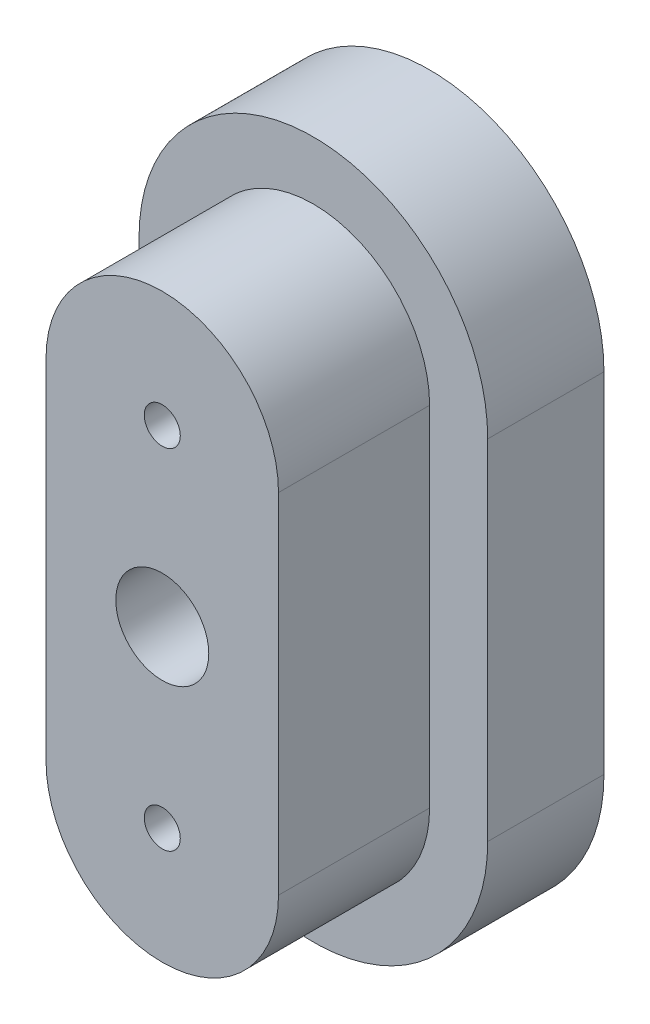
SolidWorks part; units mm, degrees
ref_plane "Front Plane" through (0, 0, 0) normal (0, 0, 1) x (1, 0, 0)
ref_plane "Top Plane" through (0, 0, 0) normal (0, 1, 0) x (1, 0, 0)
ref_plane "Right Plane" through (0, 0, 0) normal (1, 0, 0) x (0, 0, -1)
sketch "Sketch1" plane through (0, 0, 0) normal (0, 0, 1) x (1, 0, 0)
  line L0 (0, -4.7863) -> (0, 25.2137) construction
  line L1 (-10, -4.7863) -> (-10, 25.2137)
  line L2 (10, -4.7863) -> (10, 25.2137)
  arc A0 (-10, -4.7863) -> (10, -4.7863) centre (0, -4.7863) ccw
  arc A1 (10, 25.2137) -> (-10, 25.2137) centre (0, 25.2137) ccw
  point P2 (0, 10.2137)
  dimension "D1" = 0
  dimension "D2" = 30
  dimension "D3" = 10
extrude "Boss-Extrude1" add sketch "Sketch1" along normal blind 23
sketch "Sketch2" plane through (0, 0, 23) normal (0, 0, 1) x (1, 0, 0)
  line L0 (-10, 10.2137) -> (10, 10.2137) construction
  line L1 (-10, 25.2137) -> (-10, -4.7863) construction
  line L2 (10, -4.7863) -> (10, 25.2137) construction
  line L3 (0, 10.2137) -> (0, 25.2137) construction
  line L4 (0, 10.2137) -> (0, -4.7863) construction
  circle A0 centre (0, 25.2137) radius 1.55
  circle A1 centre (0, -4.7863) radius 1.55
  dimension "D1" = 3.1
  dimension "D2" = 3.1
  dimension "D4" = 15
  dimension "D5" = 15
extrude "Cut-Extrude1" cut sketch "Sketch2" against normal blind 30
sketch "Sketch3" plane through (0, 0, 0) normal (0, 0, -1) x (-1, 0, 0)
  line L0 (-10, 25.2137) -> (-10, -4.7863)
  line L1 (-10, 10.2137) -> (-15, 10.2137) construction
  line L2 (-15, 25.2137) -> (-15, -4.7863)
  line L3 (0, 35.2137) -> (0, -14.7863) construction
  line L4 (10, 25.2137) -> (10, -4.7863)
  line L5 (15, 25.2137) -> (15, -4.7863)
  arc A0 (10, 25.2137) -> (-10, 25.2137) centre (0, 25.2137) ccw construction
  arc A1 (-10, -4.7863) -> (10, -4.7863) centre (0, -4.7863) ccw construction
  arc A2 (-10, 25.2137) -> (10, 25.2137) centre (0, 25.2137) cw
  arc A3 (10, -4.7863) -> (-10, -4.7863) centre (0, -4.7863) cw
  arc A4 (-15, -4.7863) -> (15, -4.7863) centre (0, -4.7863) ccw
  arc A5 (15, 25.2137) -> (-15, 25.2137) centre (0, 25.2137) ccw
extrude "Boss-Extrude2" add sketch "Sketch3" against normal blind 10
sketch "Sketch5" plane through (0, 0, 23) normal (0, 0, 1) x (1, 0, 0)
  line L0 (10, -4.7863) -> (10, 25.2137) construction
  circle A0 centre (0, 10.2137) radius 4
  circle A2 centre (0, 25.2137) radius 1.55 construction
  dimension "D1" = 15
  dimension "D2" = 10
  dimension "D3" = 8
extrude "Cut-Extrude3" cut sketch "Sketch5" against normal blind 70
sketch "Esquisse1" plane through (0, 0, 0) normal (0, 0, -1) x (-1, 0, 0)
  circle A0 centre (0, 25.2137) radius 4.15
  circle A1 centre (0, -4.7863) radius 4.15
  dimension "D1" = 8.3
  dimension "D2" = 8.3
extrude "Enlèv. mat.-Extru.1" cut sketch "Esquisse1" against normal blind 3
